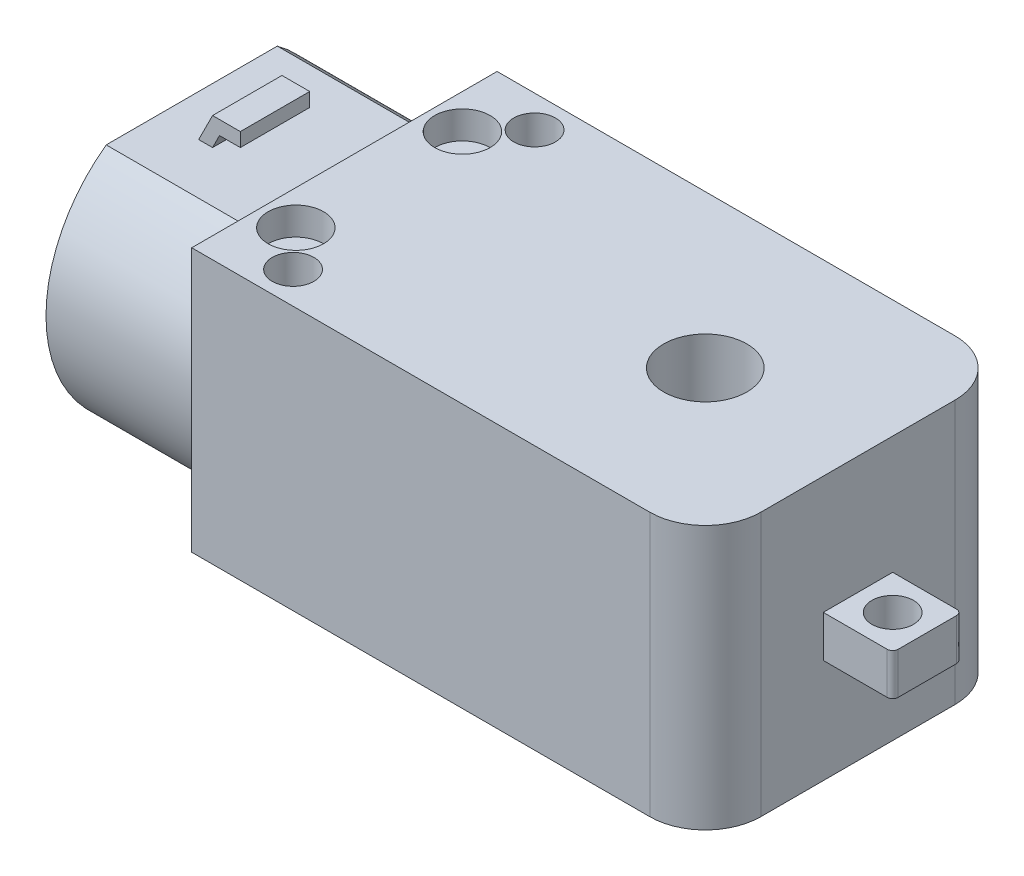
SolidWorks part; units mm, degrees
ref_plane "Front Plane" through (0, 0, 0) normal (0, 0, 1) x (1, 0, 0)
ref_plane "Top Plane" through (0, 0, 0) normal (0, 1, 0) x (1, 0, 0)
ref_plane "Right Plane" through (0, 0, 0) normal (1, 0, 0) x (0, 0, -1)
sketch "Sketch1" plane through (0, 0, 0) normal (0, 1, 0) x (1, 0, 0)
  line L1 (0, 11) -> (-37, 11)
  line L2 (0, 11) -> (0, -11)
  line L3 (0, -11) -> (-37, -11)
  line L4 (-37, 11) -> (-37, -11)
  dimension "D1" = 11
  dimension "D2" = 11
  dimension "D3" = 37
extrude "Boss-Extrude1" add sketch "Sketch1" along normal blind 10
sketch "Sketch3" plane through (0, 0, 0) normal (0, -1, 0) x (1, 0, 0)
  line L4 (0, -11) -> (0, 11)
  line L5 (0, 11) -> (-37, 11)
  line L6 (-37, 11) -> (-37, -11)
  line L7 (-37, -11) -> (0, -11)
  line L8 (0, -11) -> (0, 11)
  line L9 (0, 11) -> (-37, 11)
  line L10 (-37, 11) -> (-37, -11)
  line L11 (-37, -11) -> (0, -11)
  dimension "D1" = 0
extrude "Boss-Extrude2" add sketch "Sketch3" along normal blind 9
sketch "Sketch5" plane through (0, 0, 0) normal (1, 0, 0) x (0, 0, -1)
  line L1 (-2.5, 1.5) -> (2.5, 1.5)
  line L2 (-2.5, 1.5) -> (-2.5, -1.5)
  line L3 (-2.5, -1.5) -> (2.5, -1.5)
  line L4 (2.5, 1.5) -> (2.5, -1.5)
  line L5 (-2.5, 1.5) -> (2.5, -1.5) construction
  line L6 (-2.5, -1.5) -> (2.5, 1.5) construction
  point P0 (0, 0)
  dimension "D1" = 5
  dimension "D2" = 3
extrude "Boss-Extrude3" add sketch "Sketch5" along normal blind 5
sketch "Sketch6" plane through (0, 1.5, 0) normal (0, 1, 0) x (1, 0, 0)
  circle A0 centre (2.5, 0) radius 1.5
  dimension "D1" = 2.5
  dimension "D2" = 3
extrude "Cut-Extrude1" cut sketch "Sketch6" against normal blind 5
fillet "Fillet1" radius 0.4 2 edges at (5, 0, 2.5) (5, 0, -2.5)
fillet "Fillet2" radius 4 2 edges at (0, 0.5, 11) (0, 0.5, -11)
sketch "Sketch7" plane through (0, 10, 0) normal (0, 1, 0) x (1, 0, 0)
  line L0 (6.7722, 0) -> (-40.8799, 0) construction
  line L1 (0, -7) -> (0, 7) construction
  circle A0 centre (-11, 0) radius 3
  dimension "D1" = 6
  dimension "D2" = 11
extrude "Cut-Extrude2" cut sketch "Sketch7" against normal through all
sketch "Sketch8" plane through (0, 10, 0) normal (0, 1, 0) x (1, 0, 0)
  line L0 (-4, 11) -> (-37, 11) construction
  line L1 (-37, 11) -> (-37, -11) construction
  line L2 (8.24, 0) -> (-43.0466, 0) construction
  circle A0 centre (-32, 8.7) radius 1.5
  circle A2 centre (-35, 9) radius 1
  circle A3 centre (-34.5, 6) radius 2
  circle A4 centre (-34.5, -6) radius 2
  circle A5 centre (-32, -8.7) radius 1.5
  circle A6 centre (-35, -9) radius 1
  dimension "D3" = 3
  dimension "D6" = 2
  dimension "D7" = 4
  dimension "D1" = 2.3
  dimension "D2" = 5
  dimension "D4" = 2
  dimension "D5" = 2
  dimension "D8" = 5
  dimension "D9" = 2.5
extrude "Cut-Extrude4" cut sketch "Sketch8" against normal through all contours A0 | A5
sketch "Sketch10" plane through (0, 10, 0) normal (0, 1, 0) x (1, 0, 0)
  line L0 (-4, 11) -> (-37, 11) construction
  line L1 (-37, 11) -> (-37, -11) construction
  line L2 (-37, -11) -> (-4, -11) construction
  circle A0 centre (-34.5, 6) radius 2
  circle A1 centre (-34.5, -6) radius 2
  dimension "D2" = 4
  dimension "D4" = 4
  dimension "D1" = 5
  dimension "D3" = 2.5
  dimension "D5" = 2.5
  dimension "D6" = 5
extrude "Cut-Extrude5" cut sketch "Sketch10" against normal blind 2
sketch "Sketch11" plane through (-37, 0, 0) normal (-1, 0, 0) x (0, 0, 1)
  line L1 (-6.1644, 8.5) -> (6.1644, 8.5)
  line L3 (-6.1644, -8.5) -> (6.1644, -8.5)
  line L5 (-8.5, 8.5) -> (8.5, -8.5) construction
  line L6 (-8.5, -8.5) -> (8.5, 8.5) construction
  arc A0 (6.1644, -8.5) -> (6.1644, 8.5) centre (0, 0) ccw
  arc A1 (-6.1644, 8.5) -> (-6.1644, -8.5) centre (0, 0) ccw
  dimension "D1" = 21
  dimension "D2" = 17
  dimension "D3" = 17
extrude "Boss-Extrude4" add sketch "Sketch11" along normal blind 11
sketch "Sketch12" plane through (-48, 0, 0) normal (-1, 0, 0) x (0, 0, 1)
  line L0 (5.831, 7.5) -> (-5.831, 7.5)
  line L1 (-5.831, -7.5) -> (5.831, -7.5)
  line L2 (-6.1644, -8.5) -> (6.1644, -8.5)
  line L3 (6.1644, 8.5) -> (-6.1644, 8.5)
  line L4 (-6.1644, -8.5) -> (6.1644, -8.5)
  line L5 (6.1644, 8.5) -> (-6.1644, 8.5)
  arc A0 (-5.831, 7.5) -> (-5.831, -7.5) centre (0, 0) ccw
  arc A1 (5.831, -7.5) -> (5.831, 7.5) centre (0, 0) ccw
  arc A2 (-6.1644, 8.5) -> (-6.1644, -8.5) centre (0, 0) ccw
  arc A3 (6.1644, -8.5) -> (6.1644, 8.5) centre (0, 0) ccw
  arc A4 (-6.1644, 8.5) -> (-6.1644, -8.5) centre (0, 0) ccw
  arc A5 (6.1644, -8.5) -> (6.1644, 8.5) centre (0, 0) ccw
  dimension "D1" = 0
  dimension "D2" = 1
extrude "Cut-Extrude6" cut sketch "Sketch12" against normal blind 11 contours L1 A1 L0 A0
sketch "Sketch13" plane through (0, 8.5, 0) normal (0, 1, 0) x (1, 0, 0)
  line L0 (-37, -6.1644) -> (-37, 6.1644) construction
  line L1 (-42, 2.5) -> (-45, 2.5)
  line L2 (-42, 2.5) -> (-42, -2.5)
  line L3 (-42, -2.5) -> (-45, -2.5)
  line L4 (-45, 2.5) -> (-45, -2.5)
  point P4 (-42, 0)
  dimension "D1" = 5
  dimension "D2" = 5
  dimension "D3" = 3
  dimension "D4" = 2.5
extrude "Boss-Extrude5" add sketch "Sketch13" along normal blind 2
sketch "Sketch14" plane through (0, 0, 2.5) normal (0, 0, 1) x (1, 0, 0)
  line L0 (-44, 10.5) -> (-45, 8.5)
  line L1 (-45, 10.5) -> (-42, 10.5) construction
  line L2 (-45, 8.5) -> (-45, 10.5)
  line L3 (-45, 10.5) -> (-45, 8.5) construction
  line L4 (-45, 10.5) -> (-44, 10.5)
  line L5 (-42, 9.5) -> (-43.5, 9.5)
  line L6 (-42, 10.5) -> (-42, 8.5) construction
  line L7 (-43.5, 9.5) -> (-44, 8.5)
  line L8 (-45, 8.5) -> (-42, 8.5) construction
  line L9 (-44, 8.5) -> (-42, 8.5)
  line L10 (-42, 8.5) -> (-42, 9.5)
  line L11 (-41.4857, 9.5) -> (-45.7011, 9.5) construction
  line L12 (-44.5, 9.5) -> (-43.5, 9.5)
  line M3 (-45, 8.5) -> (-42, 8.5)
  line M4 (-42, 8.5) -> (-42, 10.5)
  line M5 (-42, 10.5) -> (-45, 10.5)
  line M6 (-45, 10.5) -> (-45, 8.5)
  dimension "D1" = 1
  dimension "D2" = 1
  dimension "D3" = 1
  dimension "D4" = 1
extrude "Cut-Extrude7" cut sketch "Sketch14" against normal through all contours L11 L0 M5 M6 | L0 L11 L2 | L5 L7 M3 M4
mirror "Mirror2" about plane through (0, 0, 0) normal (0, 1, 0) of "Boss-Extrude5"
mirror "Mirror3" about plane through (0, 0, 0) normal (0, 1, 0) of "Cut-Extrude7"
